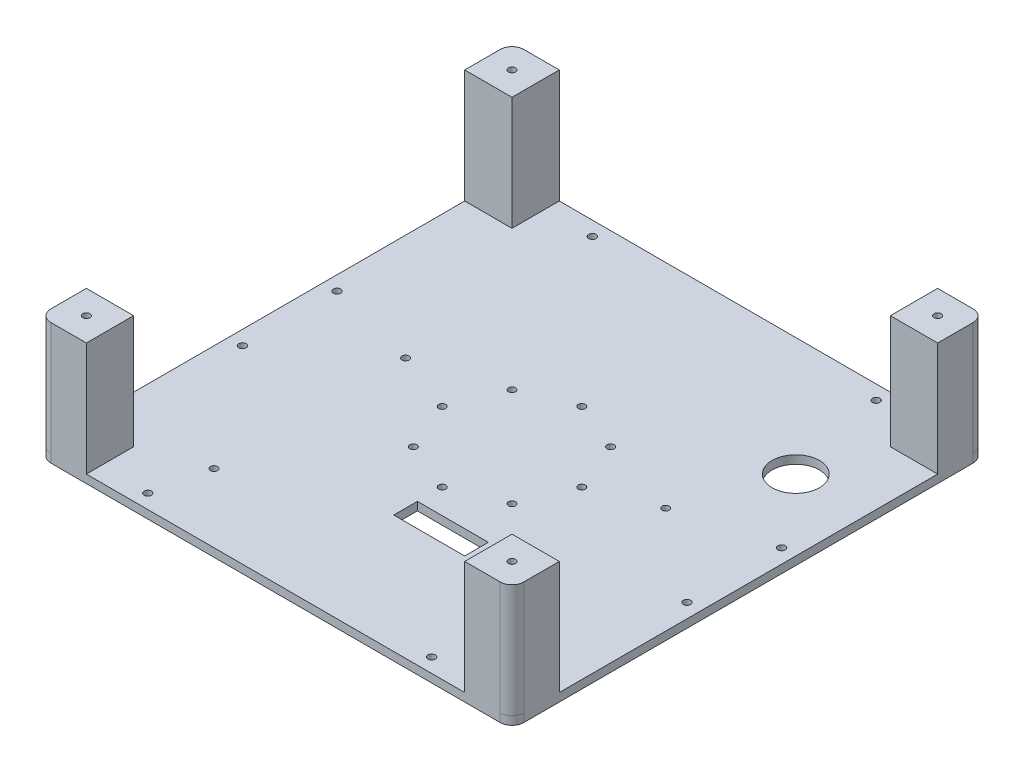
SolidWorks part; units mm, degrees
ref_plane "前视基准面" through (0, 0, 0) normal (0, 0, 1) x (1, 0, 0)
ref_plane "上视基准面" through (0, 0, 0) normal (0, 1, 0) x (1, 0, 0)
ref_plane "右视基准面" through (0, 0, 0) normal (1, 0, 0) x (0, 0, -1)
sketch "草图1" plane through (0, 0, 0) normal (0, 1, 0) x (1, 0, 0)
  line L0 (0, 100) -> (0, -100) construction
  line L1 (-100, 100) -> (100, 100)
  line L2 (-100, 100) -> (-100, -32.6875)
  line L3 (-100, -100) -> (100, -100)
  line L4 (100, 100) -> (100, -32.6875)
  line L11 (-100, -80.6875) -> (-100, -100)
  line L12 (100, -80.6875) -> (100, -100)
  line L13 (-100, 0) -> (100, 0) construction
  line L14 (100, -32.6875) -> (100, -80.6875)
  line L15 (-100, -32.6875) -> (-100, -80.6875)
  line L17 (0, -50) -> (30, -50)
  line L18 (0, -50) -> (0, -40)
  line L19 (0, -40) -> (30, -40)
  line L20 (30, -50) -> (30, -40)
  circle A6 centre (-55, 10) radius 1.5
  circle A7 centre (-55, -71) radius 1.5
  circle A8 centre (55, -71) radius 1.5
  circle A9 centre (55, 10) radius 1.5
  circle A17 centre (60, 94) radius 1.55
  circle A18 centre (60, -94) radius 1.55
  circle A19 centre (94, 20) radius 1.55
  circle A20 centre (94, -20) radius 1.55
  circle A21 centre (-60, -94) radius 1.55
  circle A22 centre (-94, -20) radius 1.55
  circle A23 centre (-94, 20) radius 1.55
  circle A24 centre (-60, 94) radius 1.55
  circle A25 centre (0, 0) radius 29.5 construction
  circle A27 centre (0, 29.5) radius 1.5
  circle A28 centre (20.8597, 20.8597) radius 1.5
  circle A29 centre (29.5, 0) radius 1.5
  circle A30 centre (20.8597, -20.8597) radius 1.5
  circle A31 centre (0, -29.5) radius 1.5
  circle A32 centre (-20.8597, -20.8597) radius 1.5
  circle A33 centre (-29.5, 0) radius 1.5
  circle A34 centre (-20.8597, 20.8597) radius 1.5
  circle A37 centre (70, 50) radius 10
  point P44 (30, -45)
  point P45 (15, -50)
  point P66 (0, 0)
  dimension "D5" = 59
  dimension "D6" = 3
  dimension "D14" = 50
  dimension "D17" = 3
  dimension "D20" = 3
  dimension "D30" = 3.1
  dimension "D32" = 3.1
  dimension "D35" = 3.1
  dimension "D7" = 8
  dimension "D8" = 20
  dimension "D10" = 50
  dimension "D1" = 200
  dimension "D2" = 200
  dimension "D3" = 100
  dimension "D4" = 100
  dimension "D9" = 70
  dimension "D11" = 30
  dimension "D12" = 10
  dimension "D13" = 70
  dimension "D18" = 55
  dimension "D19" = 90
  dimension "D21" = 81
  dimension "D22" = 55
  dimension "D29" = 6
  dimension "D31" = 60
  dimension "D33" = 6
  dimension "D34" = 60
  dimension "D36" = 6
  dimension "D37" = 20
extrude "凸台-拉伸1" add sketch "草图1" along normal blind 3.5
fillet "圆角1" radius 5 4 edges at (100, 1.75, -100) (-100, 1.75, -100) (-100, 1.75, 100) (100, 1.75, 100)
sketch "草图2" plane through (0, 3.5, 0) normal (0, 1, 0) x (1, 0, 0)
  line L0 (95, 100) -> (-95, 100) construction
  line L1 (-80, 100) -> (-100, 100)
  line L2 (-80, 100) -> (-80, 80)
  line L3 (-80, 80) -> (-100, 80)
  line L4 (-100, 100) -> (-100, 80)
  line L5 (-100, 95) -> (-100, -95) construction
  line L6 (0, 100) -> (0, -100) construction
  line L7 (-95, -100) -> (95, -100) construction
  line L8 (-100, 0) -> (100, 0) construction
  line L9 (100, -95) -> (100, 95) construction
  line L10 (80, 80) -> (100, 80)
  line L11 (80, 100) -> (80, 80)
  line L12 (80, 100) -> (100, 100)
  line L13 (100, 100) -> (100, 80)
  line L14 (80, -100) -> (80, -80)
  line L15 (80, -100) -> (100, -100)
  line L16 (100, -100) -> (100, -80)
  line L17 (80, -80) -> (100, -80)
  line L18 (-80, -80) -> (-100, -80)
  line L19 (-100, -100) -> (-100, -80)
  line L20 (-80, -100) -> (-100, -100)
  line L21 (-80, -100) -> (-80, -80)
  circle A0 centre (-90, 90) radius 1.5
  circle A1 centre (90, 90) radius 1.5
  circle A2 centre (90, -90) radius 1.5
  circle A3 centre (-90, -90) radius 1.5
  dimension "D3" = 3
  dimension "D1" = 20
  dimension "D2" = 20
  dimension "D4" = 10
  dimension "D5" = 10
extrude "凸台-拉伸2" add sketch "草图2" along normal blind 48
fillet "圆角2" radius 5 4 edges at (100, 27.5, 100) (100, 27.5, -100) (-100, 27.5, -100) (-100, 27.5, 100)
